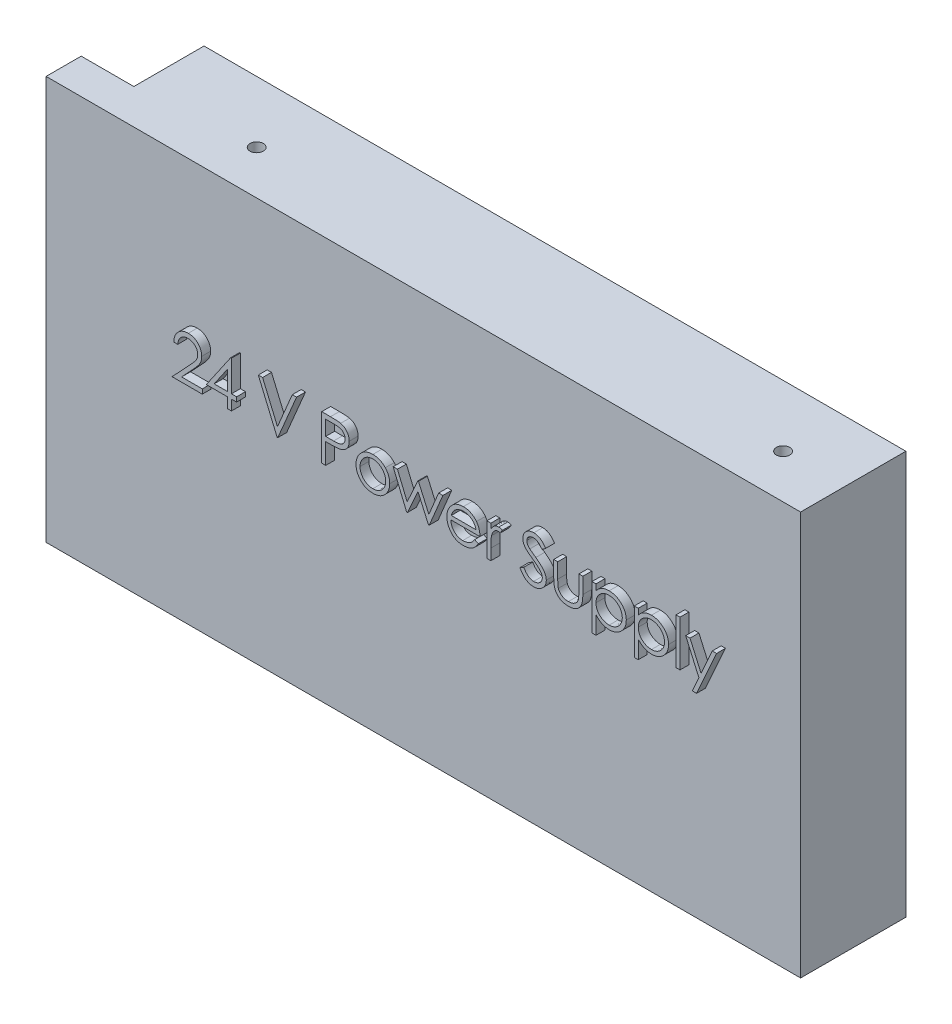
SolidWorks part; units mm, degrees
ref_plane "Front Plane" through (0, 0, 0) normal (0, 0, 1) x (1, 0, 0)
ref_plane "Top Plane" through (0, 0, 0) normal (0, 1, 0) x (1, 0, 0)
ref_plane "Right Plane" through (0, 0, 0) normal (1, 0, 0) x (0, 0, -1)
sketch "Sketch1" plane through (0, 0, 0) normal (0, 0, 1) x (1, 0, 0)
  line L1 (100, -57.5) -> (-100, -57.5)
  line L2 (100, -57.5) -> (100, 57.5)
  line L3 (100, 57.5) -> (-100, 57.5)
  line L4 (-100, -57.5) -> (-100, 57.5)
  line L5 (100, -57.5) -> (-100, 57.5) construction
  line L6 (100, 57.5) -> (-100, -57.5) construction
  point P0 (0, 0)
  dimension "D1" = 200
  dimension "D2" = 115
extrude "Boss-Extrude1" add sketch "Sketch1" along normal blind 30
sketch "Sketch2" plane through (0, 0, 30) normal (0, 0, 1) x (1, 0, 0)
  text T0 "24 V Power Supply" font "Century Gothic" height in points 48
extrude "Boss-Extrude2" add sketch "Sketch2" along normal blind 2.54
sketch "Sketch3" plane through (-100, 0, 0) normal (-1, 0, 0) x (0, 0, 1)
  line L0 (30, 57.5) -> (0, 57.5) construction
  line L1 (30, -57.5) -> (20, -57.5)
  line L2 (30, -57.5) -> (30, 57.5)
  line L3 (30, 57.5) -> (20, 57.5)
  line L4 (20, -57.5) -> (20, 57.5)
  dimension "D1" = 10
extrude "Boss-Extrude3" add sketch "Sketch3" along normal blind 15
sketch "Sketch4" plane through (0, -57.5, 0) normal (0, -1, 0) x (1, 0, 0)
  line L0 (-115, 30) -> (100, 30) construction
  line L1 (-67.5, 17.5) -> (82.5, 17.5) construction
  line L2 (-100, 20) -> (-100, 0) construction
  circle A0 centre (-67.5, 17.5) radius 1.905
  circle A3 centre (82.5, 17.5) radius 1.905
  dimension "D1" = 3.81
  dimension "D2" = 150
  dimension "D3" = 32.5
  dimension "D4" = 12.5
extrude "Cut-Extrude1" cut sketch "Sketch4" against normal through all
